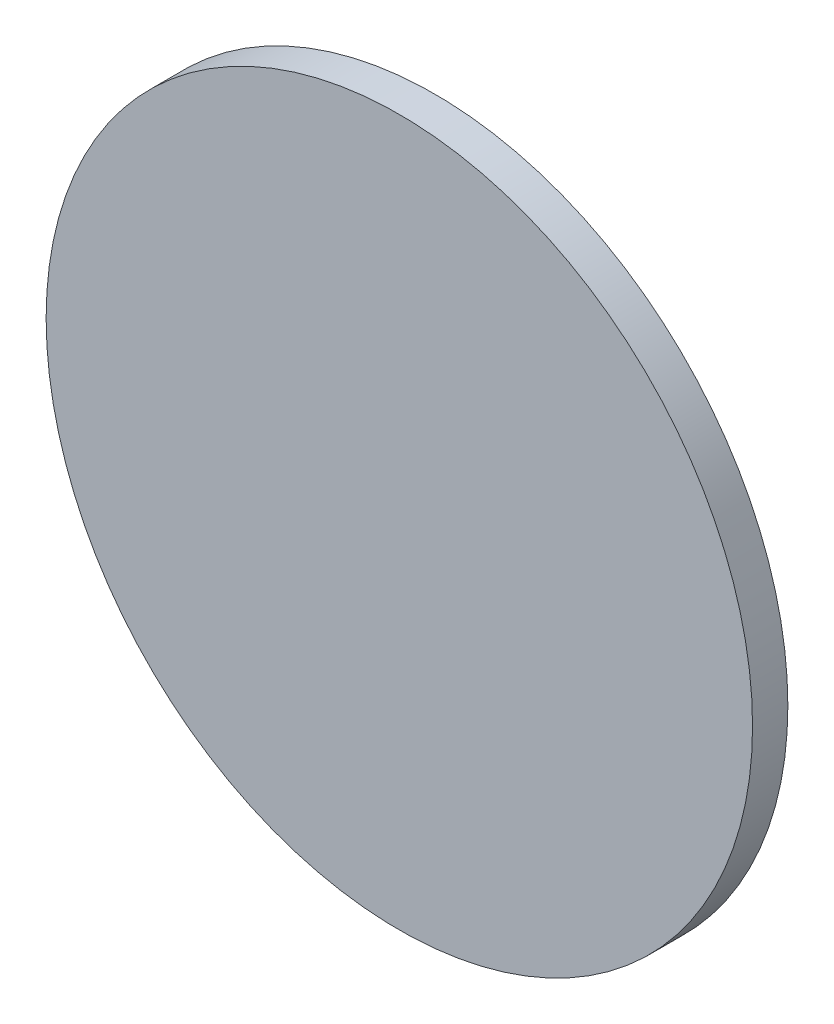
SolidWorks part; units mm, degrees
material "Custom Plastic"
ref_plane "Front Plane" through (0, 0, 0) normal (0, 0, 1) x (1, 0, 0)
ref_plane "Top Plane" through (0, 0, 0) normal (0, 1, 0) x (1, 0, 0)
ref_plane "Right Plane" through (0, 0, 0) normal (1, 0, 0) x (0, 0, -1)
sketch "Sketch1" plane through (0, 0, 0) normal (0, 0, 1) x (1, 0, 0)
  circle A0 centre (0, 0) radius 31.75
  dimension "D1" = 63.5
extrude "Boss-Extrude1" add sketch "Sketch1" along normal blind 3.175
